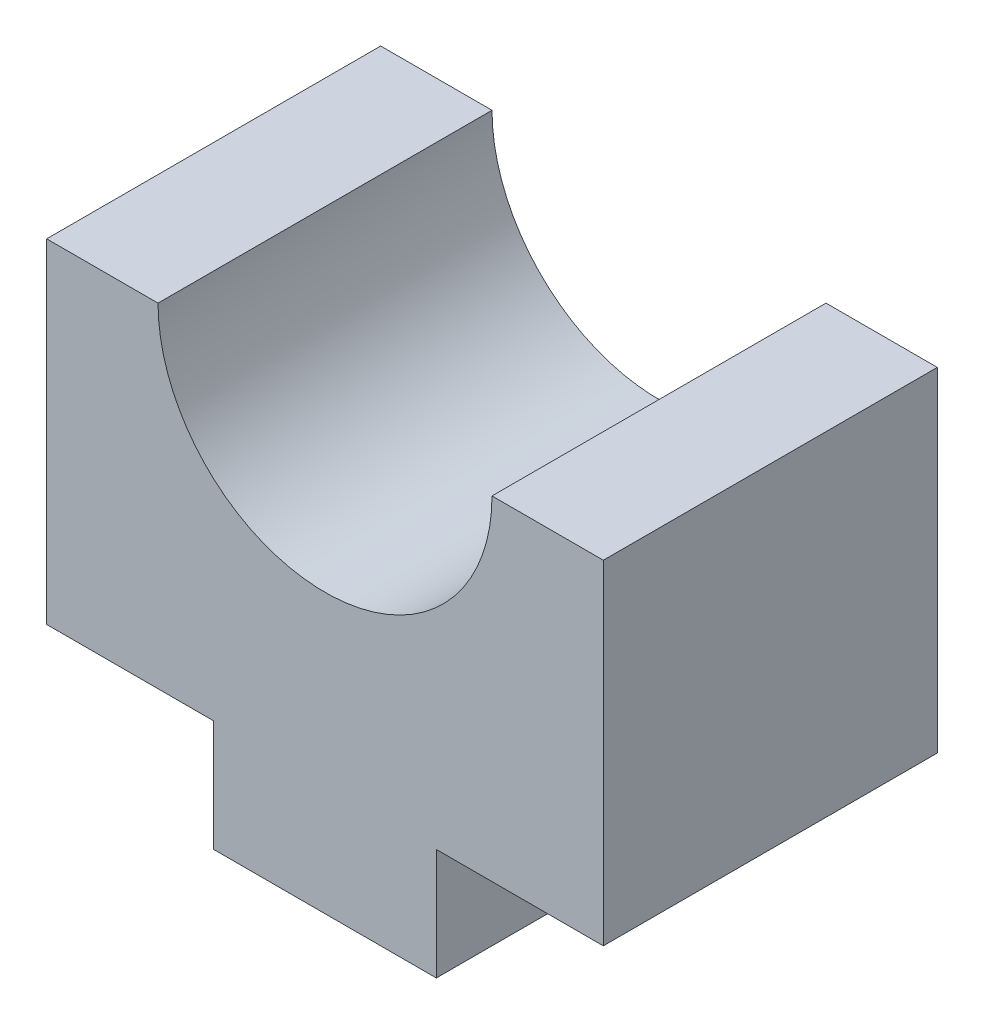
SolidWorks part; units mm, degrees
ref_plane "Alzado" through (0, 0, 0) normal (0, 0, 1) x (1, 0, 0)
ref_plane "Planta" through (0, 0, 0) normal (0, 1, 0) x (1, 0, 0)
ref_plane "Vista lateral" through (0, 0, 0) normal (1, 0, 0) x (0, 0, -1)
sketch "Croquis1" plane through (0, 0, 0) normal (0, 0, 1) x (1, 0, 0)
  line L0 (-7.5, 0) -> (7.5, 0) construction
  line L1 (7.5, 0) -> (12.5, 0)
  line L2 (12.5, 0) -> (12.5, -15)
  line L3 (12.5, -15) -> (5, -15)
  line L4 (5, -15) -> (5, -20)
  line L5 (5, -20) -> (-5, -20)
  line L6 (-5, -20) -> (-5, -15)
  line L7 (-5, -15) -> (-12.5, -15)
  line L8 (-12.5, -15) -> (-12.5, 0)
  line L9 (-12.5, 0) -> (-7.5, 0)
  arc A1 (-7.5, 0) -> (7.5, 0) centre (0, 0) ccw
  point P3 (0, -20)
  point P4 (0, 0)
  dimension "D2" = 7.5
  dimension "D1" = 15
  dimension "D3" = 7.5
  dimension "D4" = 10
  dimension "D5" = 20
  dimension "D6" = 5
  dimension "D7" = 5
extrude "Saliente-Extruir1" add sketch "Croquis1" against normal blind 15
